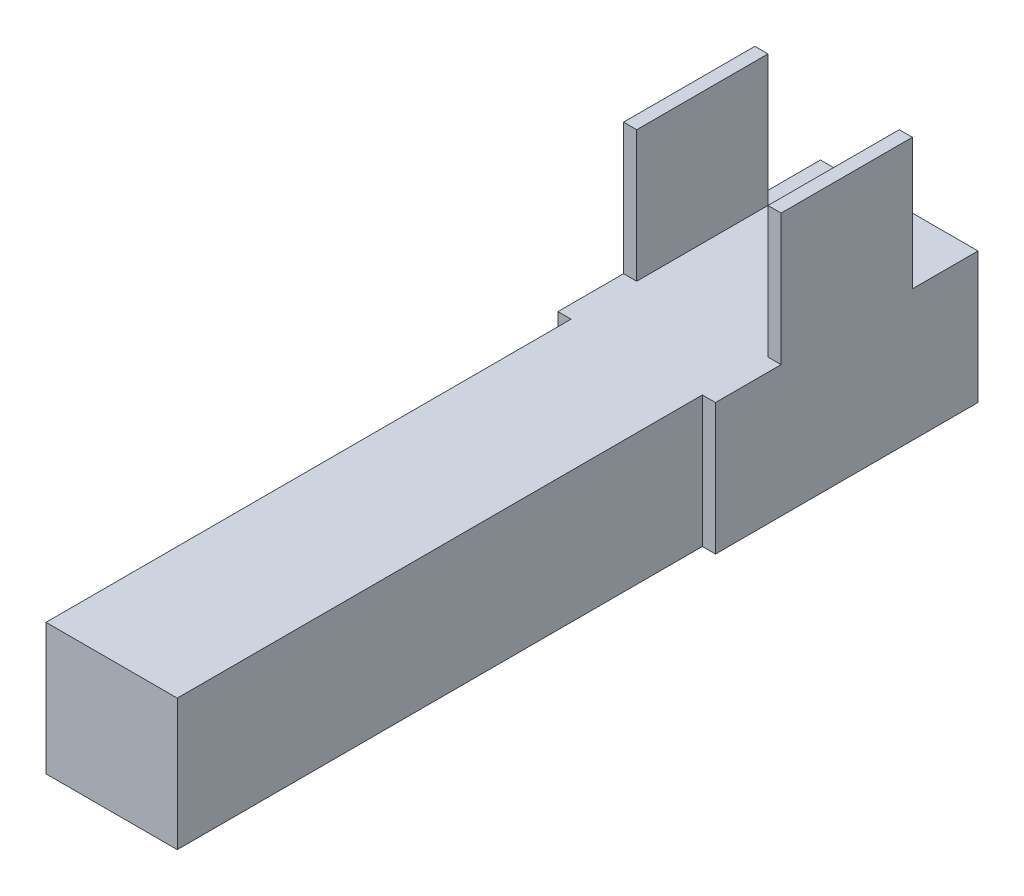
SolidWorks part; units mm, degrees
ref_plane "Front Plane" through (0, 0, 0) normal (0, 0, 1) x (1, 0, 0)
ref_plane "Top Plane" through (0, 0, 0) normal (0, 1, 0) x (1, 0, 0)
ref_plane "Right Plane" through (0, 0, 0) normal (1, 0, 0) x (0, 0, -1)
sketch "Sketch1" plane through (0, 0, 0) normal (0, 1, 0) x (1, 0, 0)
  line L1 (0, 0) -> (12.7, 0)
  line L2 (0, 0) -> (0, 152.4)
  line L3 (0, 152.4) -> (12.7, 152.4)
  line L4 (12.7, 0) -> (12.7, 152.4)
  dimension "D1" = 12.7
  dimension "D2" = 152.4
extrude "Boss-Extrude1" add sketch "Sketch1" along normal blind 25.4
sketch "Sketch6" plane through (12.7, 0, 0) normal (1, 0, 0) x (0, 0, -1)
  line L0 (0, 25.4) -> (152.4, 25.4) construction
  line L1 (152.4, 0) -> (101.6, 0)
  line L2 (152.4, 0) -> (152.4, 25.4)
  line L3 (152.4, 25.4) -> (101.6, 25.4)
  line L4 (101.6, 0) -> (101.6, 25.4)
  dimension "D1" = 50.8
extrude "Boss-Extrude5" add sketch "Sketch6" along normal blind 2.54 contours L2 L1 L4 L3
sketch "Sketch7" plane through (0, 25.4, 0) normal (0, 1, 0) x (1, 0, 0)
  line L0 (12.7, 101.6) -> (12.7, 152.4) construction
  line L1 (15.24, 152.4) -> (0, 152.4) construction
  line L3 (15.24, 152.4) -> (15.24, 101.6) construction
  line L4 (12.7, 114.3) -> (15.24, 114.3)
  line L5 (12.7, 114.3) -> (12.7, 139.7)
  line L6 (12.7, 139.7) -> (15.24, 139.7)
  line L7 (15.24, 114.3) -> (15.24, 139.7)
  point P8 (12.7, 127)
extrude "Boss-Extrude6" add sketch "Sketch7" along normal blind 25.4
mirror "Mirror1" about plane through (0, 25.4, 0) normal (1, 0, 0) of "Boss-Extrude6", "Boss-Extrude1", "Boss-Extrude5"
